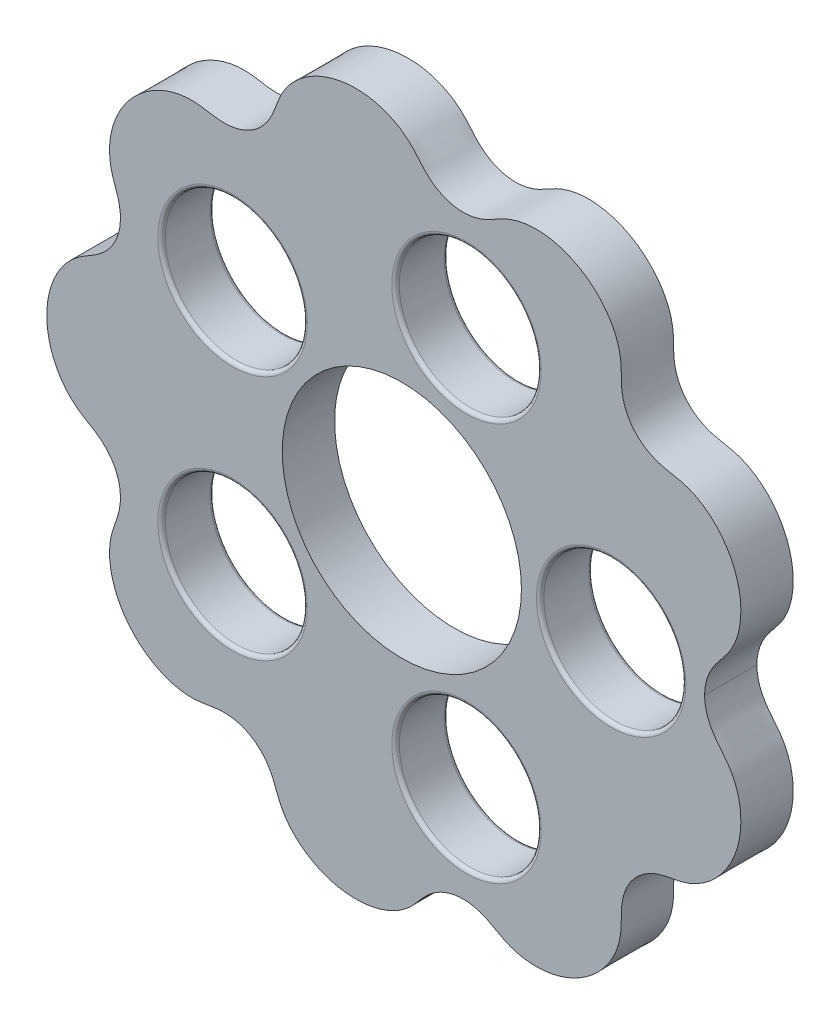
SolidWorks part; units mm, degrees
ref_plane "Front Plane" through (0, 0, 0) normal (0, 0, 1) x (1, 0, 0)
ref_plane "Top Plane" through (0, 0, 0) normal (0, 1, 0) x (1, 0, 0)
ref_plane "Right Plane" through (0, 0, 0) normal (1, 0, 0) x (0, 0, -1)
sketch "Sketch5" plane through (0, 0, 0) normal (0, 0, 1) x (1, 0, 0)
  line L0 (56.1295, 0) -> (-56.1295, 0) construction
  spline S0 degree 4 poles (43.9675, 24.717) (44.1687, 24.5903) (44.5645, 24.3264) (45.3286, 23.7583) (46.2192, 22.9456) (47.0351, 22.0389) (47.767, 21.0472) (48.3047, 20.1937) (48.7789, 19.3035) (49.1875, 18.3813) (49.5288, 17.4321) (49.8009, 16.4608) (50.0022, 15.4725) (50.1309, 14.4718) (50.1857, 13.465) (50.1646, 12.4557) (50.0754, 11.5375) (49.9355, 10.7086) (49.7662, 9.9782) (49.6126, 9.4514) (49.4889, 9.0812) (49.4028, 8.8445) (49.3404, 8.6786) (49.2593, 8.4723) (49.2112, 8.355) (49.1184, 8.1404) (49.0342, 7.9528) (48.9526, 7.7785) (48.8555, 7.5808) (48.7377, 7.3519) (48.5852, 7.0696) (48.3939, 6.7364) (48.159, 6.3539) (47.8783, 5.925) (47.5899, 5.501) (47.272, 5.0371) (46.9336, 4.5268) (46.4972, 3.8088) (46.0481, 2.9005) (45.6825, 1.8227) (45.4869, 0.6102) (45.484, -0.5297) (45.6482, -1.6249) (45.9563, -2.6553) (46.3957, -3.633) (46.9384, -4.5527) (47.5411, -5.4294) (48.1406, -6.3054) (48.6904, -7.2258) (49.1655, -8.1979) (49.6395, -9.4396) (50.0276, -10.9696) (50.2323, -12.8006) (50.1376, -14.9024) (49.7158, -16.999) (48.9654, -19.0387) (47.6825, -21.3439) (46.1225, -23.1584) (44.4622, -24.4809) (42.8636, -25.3575) (41.8693, -25.7911) (40.8609, -26.1347) (39.8537, -26.4142) (38.8354, -26.6988) (37.8273, -27.0594) (36.854, -27.5373) (35.9432, -28.1497) (34.939, -29.061) (34.1314, -30.1487) (33.5539, -31.3627) (33.1995, -32.6385) (33.0289, -33.6766) (32.9288, -34.7173) (32.8268, -35.7531) (32.6605, -36.8007) (32.4035, -37.8498) (31.9667, -39.1228) (31.2657, -40.5767) (30.227, -42.1296) (28.7855, -43.6836) (27.1062, -45.0123) (25.2246, -46.0808) (22.759, -47.0129) (20.3921, -47.3918) (18.2669, -47.3281) (16.4777, -46.9628) (15.4371, -46.6501) (14.4437, -46.2601) (13.4918, -45.8241) (12.526, -45.3893) (11.5179, -45.0232) (10.4613, -44.7719) (9.3672, -44.6655) (8.0168, -44.7313) (6.7093, -45.0558) (5.5003, -45.619) (4.4257, -46.3648) (3.6406, -47.0418) (2.7268, -47.9414) (1.7917, -48.8513) (0.7375, -49.6733) (-0.6219, -50.4978) (-2.0723, -51.1567) (-3.833, -51.6803) (-5.8932, -51.9573) (-7.9905, -51.9206) (-10.0775, -51.5666) (-12.088, -50.903) (-13.9742, -49.9397) (-15.4824, -48.8394) (-16.6398, -47.7163) (-17.4875, -46.6721) (-18.0894, -45.7762) (-18.6055, -44.8504) (-19.0563, -43.9131) (-19.505, -42.9697) (-20.0175, -42.052) (-20.7823, -40.9724) (-21.7356, -40.0254) (-22.8628, -39.2744) (-24.1159, -38.7557) (-25.181, -38.4871) (-26.2594, -38.3667) (-27.331, -38.3696) (-28.3861, -38.4493) (-29.4288, -38.5322) (-30.4948, -38.5564) (-31.5784, -38.4915) (-33.3824, -38.2183) (-35.3977, -37.547) (-37.488, -36.3782) (-39.4819, -34.6563) (-40.8817, -33.0063) (-42.0024, -31.1805) (-42.8224, -29.2237) (-43.2634, -27.4068) (-43.4214, -25.7988) (-43.3867, -24.1917) (-43.2006, -22.8598) (-42.8734, -21.5791) (-42.5465, -20.3141) (-42.3555, -19.2784) (-42.2772, -18.2222) (-42.3378, -17.1586) (-42.5473, -16.1081) (-42.909, -15.0934) (-43.4171, -14.138) (-44.0594, -13.2614) (-44.8022, -12.4895) (-45.614, -11.8151) (-46.4585, -11.2086) (-47.2938, -10.6137) (-48.1184, -9.9558) (-48.9082, -9.2134) (-49.6274, -8.4019) (-50.27, -7.5287) (-50.8209, -6.6283) (-51.2848, -5.7121) (-51.6811, -4.7493) (-52.0054, -3.745) (-52.2537, -2.7045) (-52.4219, -1.6338) (-52.5132, -0.4683) (-52.5053, 0.6082) (-52.4229, 1.588) (-52.2881, 2.4676) (-52.1443, 3.1648) (-51.9645, 3.8537) (-51.7758, 4.4473) (-51.5919, 4.9485) (-51.4091, 5.3965) (-51.2326, 5.7933) (-51.0254, 6.2185) (-50.7825, 6.6702) (-50.5225, 7.111) (-50.2433, 7.5422) (-49.9859, 7.9069) (-49.7512, 8.2152) (-49.5733, 8.4365) (-49.4505, 8.5837) (-49.3167, 8.7389) (-49.1732, 8.9007) (-49.0859, 8.996) (-48.9341, 9.1566) (-48.7865, 9.3083) (-48.6467, 9.4473) (-48.4833, 9.6035) (-48.2876, 9.7838) (-48.0399, 10.0026) (-47.7361, 10.2569) (-47.3725, 10.5432) (-46.9482, 10.8582) (-46.5187, 11.1664) (-46.0586, 11.4965) (-45.5745, 11.8581) (-44.9448, 12.3709) (-44.2444, 13.0481) (-43.5571, 13.907) (-42.9254, 15.0287) (-42.4873, 16.2586) (-42.2842, 17.5197) (-42.2956, 18.7647) (-42.4587, 19.9025) (-42.6702, 20.801) (-42.8707, 21.5656) (-42.9963, 22.0776) (-43.0549, 22.3346) (-43.083, 22.4633) knots 0 0 0 0 0 0.004209 0.008419 0.016838 0.021298 0.025758 0.030218 0.034678 0.039138 0.043598 0.048058 0.052519 0.056979 0.061439 0.065899 0.070359 0.073315 0.076272 0.079229 0.079968 0.080337 0.080707 0.082185 0.08332 0.083887 0.084454 0.085589 0.086723 0.087857 0.088992 0.091261 0.09353 0.095799 0.098067 0.100336 0.103486 0.106636 0.112936 0.118237 0.123537 0.128285 0.133033 0.137774 0.142514 0.147212 0.151909 0.156607 0.161304 0.166171 0.171038 0.180103 0.189168 0.198651 0.208135 0.217812 0.227489 0.245161 0.250125 0.255089 0.259714 0.26434 0.268966 0.273592 0.278429 0.283265 0.28811 0.292954 0.30235 0.307042 0.311735 0.31634 0.320946 0.325551 0.330156 0.335099 0.340042 0.349343 0.358644 0.368028 0.377413 0.387105 0.396798 0.414499 0.419471 0.424443 0.429077 0.433711 0.438344 0.442978 0.447822 0.452667 0.457519 0.462371 0.47167 0.476315 0.480961 0.485476 0.489992 0.499022 0.504042 0.509062 0.518101 0.527139 0.536428 0.545716 0.555093 0.56447 0.573764 0.583058 0.587998 0.592937 0.597539 0.602141 0.606743 0.611345 0.616033 0.620722 0.63011 0.634958 0.639806 0.644647 0.649487 0.654116 0.658746 0.663375 0.668005 0.672972 0.67794 0.695625 0.70531 0.714994 0.724386 0.733779 0.743088 0.752398 0.757345 0.762292 0.771511 0.77612 0.78073 0.785426 0.790123 0.794825 0.799527 0.804326 0.809124 0.813913 0.818702 0.82324 0.827778 0.832317 0.836855 0.841899 0.846943 0.851483 0.856023 0.860563 0.865103 0.869895 0.874687 0.879479 0.884271 0.89057 0.893719 0.896868 0.900017 0.903166 0.906315 0.90789 0.909465 0.911732 0.913999 0.916266 0.918534 0.920801 0.923068 0.924202 0.925335 0.925902 0.926469 0.927603 0.928772 0.929357 0.929942 0.931111 0.932281 0.933451 0.93462 0.936959 0.939299 0.941638 0.943977 0.946316 0.949324 0.952331 0.958347 0.96353 0.968712 0.975025 0.981338 0.986003 0.990669 0.995334 0.997667 1 1 1 1 1 construction
  spline S1 degree 4 poles (45.5, 0) (45.5, -0.2738) (45.5269, -0.8158) (45.6466, -1.6196) (45.9563, -2.6553) (46.3957, -3.633) (46.9384, -4.5527) (47.5411, -5.4294) (48.1406, -6.3054) (48.6904, -7.2258) (49.1655, -8.1979) (49.6395, -9.4396) (50.0276, -10.9696) (50.2323, -12.8006) (50.1376, -14.9024) (49.7158, -16.999) (48.9654, -19.0387) (47.6825, -21.3439) (46.1225, -23.1584) (44.4622, -24.4809) (42.8636, -25.3575) (41.8693, -25.7911) (40.8609, -26.1347) (39.8537, -26.4142) (38.8354, -26.6988) (37.8273, -27.0594) (36.854, -27.5373) (35.9432, -28.1497) (34.939, -29.061) (34.1314, -30.1487) (33.5539, -31.3627) (33.1995, -32.6385) (33.0289, -33.6766) (32.9288, -34.7173) (32.8268, -35.7531) (32.6605, -36.8007) (32.4035, -37.8498) (31.9667, -39.1228) (31.2657, -40.5767) (30.227, -42.1296) (28.7855, -43.6836) (27.1062, -45.0123) (25.2246, -46.0808) (22.759, -47.0129) (20.3921, -47.3918) (18.2669, -47.3281) (16.4777, -46.9628) (15.4371, -46.6501) (14.4437, -46.2601) (13.4918, -45.8241) (12.526, -45.3893) (11.5179, -45.0232) (10.4613, -44.7719) (9.3672, -44.6655) (8.0168, -44.7313) (6.7093, -45.0558) (5.5003, -45.619) (4.4257, -46.3648) (3.6406, -47.0418) (2.7268, -47.9414) (1.7917, -48.8513) (0.7375, -49.6733) (-0.6219, -50.4978) (-2.0723, -51.1567) (-3.833, -51.6803) (-5.8932, -51.9573) (-7.9905, -51.9206) (-10.0775, -51.5666) (-12.088, -50.903) (-13.9742, -49.9397) (-15.4824, -48.8394) (-16.6398, -47.7163) (-17.4875, -46.6721) (-18.0894, -45.7762) (-18.6055, -44.8504) (-19.0563, -43.9131) (-19.505, -42.9697) (-20.0175, -42.052) (-20.7823, -40.9724) (-21.7356, -40.0254) (-22.8628, -39.2744) (-24.1159, -38.7557) (-25.181, -38.4871) (-26.2594, -38.3667) (-27.331, -38.3696) (-28.3861, -38.4493) (-29.4288, -38.5322) (-30.4948, -38.5564) (-31.5784, -38.4915) (-33.3824, -38.2183) (-35.3977, -37.547) (-37.488, -36.3782) (-39.4819, -34.6563) (-40.8817, -33.0063) (-42.0024, -31.1805) (-42.8224, -29.2237) (-43.2634, -27.4068) (-43.4214, -25.7988) (-43.3867, -24.1917) (-43.2006, -22.8598) (-42.8734, -21.5791) (-42.5465, -20.3141) (-42.3555, -19.2784) (-42.2772, -18.2222) (-42.3378, -17.1586) (-42.5473, -16.1081) (-42.909, -15.0934) (-43.4171, -14.138) (-44.0594, -13.2614) (-44.8022, -12.4895) (-45.614, -11.8151) (-46.4585, -11.2086) (-47.2938, -10.6137) (-48.1184, -9.9558) (-48.9082, -9.2134) (-49.6274, -8.4019) (-50.27, -7.5287) (-50.8209, -6.6283) (-51.2848, -5.7121) (-51.6811, -4.7493) (-52.0054, -3.745) (-52.3172, -2.4382) (-52.4578, -1.3591) (-52.5, -0.5442) (-52.5, 0) knots 0.123439 0.123439 0.123439 0.123439 0.123439 0.128285 0.133033 0.137774 0.142514 0.147212 0.151909 0.156607 0.161304 0.166171 0.171038 0.180103 0.189168 0.198651 0.208135 0.217812 0.227489 0.245161 0.250125 0.255089 0.259714 0.26434 0.268966 0.273592 0.278429 0.283265 0.28811 0.292954 0.30235 0.307042 0.311735 0.31634 0.320946 0.325551 0.330156 0.335099 0.340042 0.349343 0.358644 0.368028 0.377413 0.387105 0.396798 0.414499 0.419471 0.424443 0.429077 0.433711 0.438344 0.442978 0.447822 0.452667 0.457519 0.462371 0.47167 0.476315 0.480961 0.485476 0.489992 0.499022 0.504042 0.509062 0.518101 0.527139 0.536428 0.545716 0.555093 0.56447 0.573764 0.583058 0.587998 0.592937 0.597539 0.602141 0.606743 0.611345 0.616033 0.620722 0.63011 0.634958 0.639806 0.644647 0.649487 0.654116 0.658746 0.663375 0.668005 0.672972 0.67794 0.695625 0.70531 0.714994 0.724386 0.733779 0.743088 0.752398 0.757345 0.762292 0.771511 0.77612 0.78073 0.785426 0.790123 0.794825 0.799527 0.804326 0.809124 0.813913 0.818702 0.82324 0.827778 0.832317 0.836855 0.841899 0.846943 0.851483 0.856023 0.860563 0.865103 0.869895 0.874687 0.884321 0.884321 0.884321 0.884321 0.884321 construction
  spline S2 degree 4 poles (45.5, 0) (45.5, 0.2738) (45.5269, 0.8158) (45.6466, 1.6196) (45.9563, 2.6553) (46.3957, 3.633) (46.9384, 4.5527) (47.5411, 5.4294) (48.1406, 6.3054) (48.6904, 7.2258) (49.1655, 8.1979) (49.6395, 9.4396) (50.0276, 10.9696) (50.2323, 12.8006) (50.1376, 14.9024) (49.7158, 16.999) (48.9654, 19.0387) (47.6825, 21.3439) (46.1225, 23.1584) (44.4622, 24.4809) (42.8636, 25.3575) (41.8693, 25.7911) (40.8609, 26.1347) (39.8537, 26.4142) (38.8354, 26.6988) (37.8273, 27.0594) (36.854, 27.5373) (35.9432, 28.1497) (34.939, 29.061) (34.1314, 30.1487) (33.5539, 31.3627) (33.1995, 32.6385) (33.0289, 33.6766) (32.9288, 34.7173) (32.8268, 35.7531) (32.6605, 36.8007) (32.4035, 37.8498) (31.9667, 39.1228) (31.2657, 40.5767) (30.227, 42.1296) (28.7855, 43.6836) (27.1062, 45.0123) (25.2246, 46.0808) (22.759, 47.0129) (20.3921, 47.3918) (18.2669, 47.3281) (16.4777, 46.9628) (15.4371, 46.6501) (14.4437, 46.2601) (13.4918, 45.8241) (12.526, 45.3893) (11.5179, 45.0232) (10.4613, 44.7719) (9.3672, 44.6655) (8.0168, 44.7313) (6.7093, 45.0558) (5.5003, 45.619) (4.4257, 46.3648) (3.6406, 47.0418) (2.7268, 47.9414) (1.7917, 48.8513) (0.7375, 49.6733) (-0.6219, 50.4978) (-2.0723, 51.1567) (-3.833, 51.6803) (-5.8932, 51.9573) (-7.9905, 51.9206) (-10.0775, 51.5666) (-12.088, 50.903) (-13.9742, 49.9397) (-15.4824, 48.8394) (-16.6398, 47.7163) (-17.4875, 46.6721) (-18.0894, 45.7762) (-18.6055, 44.8504) (-19.0563, 43.9131) (-19.505, 42.9697) (-20.0175, 42.052) (-20.7823, 40.9724) (-21.7356, 40.0254) (-22.8628, 39.2744) (-24.1159, 38.7557) (-25.181, 38.4871) (-26.2594, 38.3667) (-27.331, 38.3696) (-28.3861, 38.4493) (-29.4288, 38.5322) (-30.4948, 38.5564) (-31.5784, 38.4915) (-33.3824, 38.2183) (-35.3977, 37.547) (-37.488, 36.3782) (-39.4819, 34.6563) (-40.8817, 33.0063) (-42.0024, 31.1805) (-42.8224, 29.2237) (-43.2634, 27.4068) (-43.4214, 25.7988) (-43.3867, 24.1917) (-43.2006, 22.8598) (-42.8734, 21.5791) (-42.5465, 20.3141) (-42.3555, 19.2784) (-42.2772, 18.2222) (-42.3378, 17.1586) (-42.5473, 16.1081) (-42.909, 15.0934) (-43.4171, 14.138) (-44.0594, 13.2614) (-44.8022, 12.4895) (-45.614, 11.8151) (-46.4585, 11.2086) (-47.2938, 10.6137) (-48.1184, 9.9558) (-48.9082, 9.2134) (-49.6274, 8.4019) (-50.27, 7.5287) (-50.8209, 6.6283) (-51.2848, 5.7121) (-51.6811, 4.7493) (-52.0054, 3.745) (-52.3172, 2.4382) (-52.4578, 1.3591) (-52.5, 0.5442) (-52.5, 0) knots 0.123439 0.123439 0.123439 0.123439 0.123439 0.128285 0.133033 0.137774 0.142514 0.147212 0.151909 0.156607 0.161304 0.166171 0.171038 0.180103 0.189168 0.198651 0.208135 0.217812 0.227489 0.245161 0.250125 0.255089 0.259714 0.26434 0.268966 0.273592 0.278429 0.283265 0.28811 0.292954 0.30235 0.307042 0.311735 0.31634 0.320946 0.325551 0.330156 0.335099 0.340042 0.349343 0.358644 0.368028 0.377413 0.387105 0.396798 0.414499 0.419471 0.424443 0.429077 0.433711 0.438344 0.442978 0.447822 0.452667 0.457519 0.462371 0.47167 0.476315 0.480961 0.485476 0.489992 0.499022 0.504042 0.509062 0.518101 0.527139 0.536428 0.545716 0.555093 0.56447 0.573764 0.583058 0.587998 0.592937 0.597539 0.602141 0.606743 0.611345 0.616033 0.620722 0.63011 0.634958 0.639806 0.644647 0.649487 0.654116 0.658746 0.663375 0.668005 0.672972 0.67794 0.695625 0.70531 0.714994 0.724386 0.733779 0.743088 0.752398 0.757345 0.762292 0.771511 0.77612 0.78073 0.785426 0.790123 0.794825 0.799527 0.804326 0.809124 0.813913 0.818702 0.82324 0.827778 0.832317 0.836855 0.841899 0.846943 0.851483 0.856023 0.860563 0.865103 0.869895 0.874687 0.884321 0.884321 0.884321 0.884321 0.884321
  spline S3 degree 4 poles (39.5766, 22.3085) (39.8004, 22.1855) (40.2393, 21.9239) (40.8701, 21.4868) (41.6504, 20.8253) (42.3931, 20.0658) (43.0854, 19.2087) (43.7136, 18.2559) (44.194, 17.3414) (44.5404, 16.5271) (44.8328, 15.6925) (45.0308, 14.9822) (45.1819, 14.2605) (45.3056, 13.3848) (45.3599, 12.6494) (45.3641, 11.912) (45.3135, 11.1209) (45.2271, 10.4253) (45.1019, 9.7816) (44.9473, 9.1927) (44.8074, 8.7572) (44.7044, 8.4704) (44.6232, 8.2616) (44.5625, 8.1149) (44.4976, 7.9642) (44.4318, 7.8165) (44.3851, 7.7164) (44.3122, 7.5671) (44.235, 7.4141) (44.1585, 7.2686) (44.0705, 7.1098) (43.9641, 6.9272) (43.8252, 6.7007) (43.651, 6.435) (43.4364, 6.1323) (43.1781, 5.7961) (42.9105, 5.4674) (42.5879, 5.0811) (42.2182, 4.6306) (41.7093, 3.9521) (41.166, 3.0382) (40.722, 1.923) (40.4882, 0.6701) (40.4796, -0.4914) (40.653, -1.5793) (40.9703, -2.5716) (41.5084, -3.6724) (42.3244, -4.8199) (43.4581, -6.04) (44.4394, -7.6395) (45.0781, -9.416) (45.3935, -11.3531) (45.3733, -13.3153) (45.0109, -15.3119) (44.2879, -17.2786) (43.2692, -19.036) (42.0084, -20.545) (40.7094, -21.6461) (39.4845, -22.3999) (38.3839, -22.8844) (37.4599, -23.1769) (36.3352, -23.4155) (35.1998, -23.589) (34.0478, -23.9056) (32.6897, -24.5345) (31.4105, -25.469) (30.4061, -26.7091) (29.759, -28.1519) (29.4231, -29.5922) (29.3287, -30.9744) (29.4038, -32.6176) (29.1221, -34.4497) (28.4703, -36.2081) (27.4614, -37.895) (26.1801, -39.3847) (24.608, -40.684) (22.771, -41.7281) (20.842, -42.4149) (18.8892, -42.7494) (17.1745, -42.7433) (15.7452, -42.5178) (14.5921, -42.1671) (13.7044, -41.7878) (12.7082, -41.2467) (11.5114, -40.5262) (9.9117, -39.8725) (7.8846, -39.6519) (6.0646, -40.0262) (4.6603, -40.7212) (3.5017, -41.5984) (2.5562, -42.5823) (1.5724, -43.868) (0.2013, -45.0812) (-1.4073, -46.0098) (-3.2386, -46.6589) (-5.1527, -46.988) (-7.1616, -46.9931) (-9.2067, -46.6457) (-11.1104, -45.9727) (-12.8232, -45.0159) (-14.3493, -43.7814) (-15.5652, -42.3575) (-16.462, -40.738) (-16.9556, -39.1709) (-17.5096, -37.9041) (-18.1696, -36.8831) (-18.8559, -36.0951) (-19.8582, -35.2473) (-21.2523, -34.4926) (-22.7663, -34.1275) (-24.2685, -34.1297) (-25.4483, -34.294) (-26.3216, -34.4559) (-27.2413, -34.588) (-28.2108, -34.6329) (-29.4128, -34.5578) (-30.8244, -34.272) (-32.4254, -33.6847) (-34.1307, -32.7001) (-35.6958, -31.3961) (-37.0554, -29.7901) (-38.0832, -28.0317) (-38.7746, -26.1887) (-39.1404, -24.2544) (-39.1456, -22.3756) (-38.7743, -20.5568) (-38.1381, -19.037) (-37.7608, -17.7012) (-37.592, -16.2294) (-37.7184, -14.6458) (-38.2538, -13.1318) (-39.1565, -11.8152) (-40.2312, -10.7698) (-41.3844, -9.9676) (-42.6302, -9.3285) (-43.7677, -8.5031) (-44.6232, -7.6775) (-45.2512, -6.9289) (-45.782, -6.1595) (-46.2253, -5.3838) (-46.6211, -4.5372) (-46.9589, -3.6209) (-47.227, -2.6387) (-47.4135, -1.5955) (-47.5127, -0.4796) (-47.5058, 0.7018) (-47.3905, 1.7752) (-47.1986, 2.7327) (-46.9805, 3.5162) (-46.7711, 4.1323) (-46.547, 4.6862) (-46.3169, 5.1795) (-46.089, 5.6145) (-45.87, 5.994) (-45.6357, 6.364) (-45.3857, 6.7241) (-45.1543, 7.0288) (-44.9446, 7.2843) (-44.7866, 7.4663) (-44.6733, 7.5912) (-44.5523, 7.7203) (-44.4331, 7.844) (-44.354, 7.9233) (-44.2358, 8.0374) (-44.1157, 8.1505) (-43.998, 8.258) (-43.8285, 8.4062) (-43.5924, 8.6013) (-43.3085, 8.819) (-42.9747, 9.053) (-42.6316, 9.2747) (-42.2825, 9.4857) (-41.8549, 9.7349) (-41.3528, 10.0287) (-40.6295, 10.4901) (-39.795, 11.1552) (-38.9909, 12.0337) (-38.2898, 13.177) (-37.829, 14.3966) (-37.6286, 15.5914) (-37.6363, 16.7071) (-37.781, 17.6865) (-37.97, 18.4203) (-38.1733, 19.0363) (-38.3193, 19.4432) (-38.392, 19.6467) (-38.4284, 19.7485) knots 0 0 0 0 0 0.004925 0.00985 0.014774 0.019699 0.025382 0.031065 0.036747 0.039589 0.04243 0.048113 0.050954 0.053796 0.059478 0.06232 0.065161 0.069076 0.07299 0.074947 0.076905 0.077883 0.078862 0.079351 0.079841 0.080819 0.081841 0.082352 0.082863 0.083884 0.084906 0.085928 0.08695 0.088993 0.091037 0.09308 0.095124 0.097167 0.100743 0.104319 0.11147 0.117607 0.123744 0.128753 0.133762 0.138765 0.143768 0.152292 0.160815 0.170819 0.179647 0.188474 0.198478 0.208482 0.218584 0.228686 0.237453 0.246219 0.25127 0.25632 0.260596 0.264872 0.273424 0.278472 0.283519 0.293637 0.303708 0.308735 0.313762 0.322052 0.330342 0.340399 0.3492 0.358001 0.368058 0.378115 0.388332 0.398548 0.407341 0.416134 0.421242 0.426349 0.430533 0.434718 0.443086 0.453298 0.46353 0.473409 0.47834 0.48327 0.491457 0.499644 0.509508 0.518286 0.527063 0.536928 0.546792 0.556835 0.566878 0.575666 0.584455 0.594499 0.602778 0.611057 0.616076 0.621094 0.626123 0.631151 0.641282 0.65139 0.655673 0.659955 0.664238 0.66852 0.673578 0.678635 0.687414 0.696193 0.706309 0.716425 0.726499 0.736573 0.745388 0.754204 0.764278 0.772581 0.780884 0.78592 0.790956 0.801044 0.811264 0.816368 0.821471 0.829854 0.838237 0.843339 0.848442 0.852744 0.857045 0.861347 0.865648 0.870751 0.875853 0.880956 0.886058 0.892329 0.898599 0.901735 0.90487 0.908005 0.911141 0.913252 0.915363 0.917475 0.919586 0.921698 0.923809 0.924865 0.92592 0.926448 0.926976 0.928032 0.929015 0.929507 0.929999 0.930983 0.931966 0.933934 0.935901 0.937868 0.939836 0.941803 0.94377 0.947412 0.951054 0.958338 0.964286 0.970233 0.976779 0.983325 0.987494 0.991663 0.995831 0.997916 1 1 1 1 1 construction
  spline S4 degree 4 poles (40.5, 0) (40.5, -0.2667) (40.5277, -0.7931) (40.6509, -1.5727) (40.9703, -2.5716) (41.5084, -3.6724) (42.3244, -4.8199) (43.4581, -6.04) (44.4394, -7.6395) (45.0781, -9.416) (45.3935, -11.3531) (45.3733, -13.3153) (45.0109, -15.3119) (44.2879, -17.2786) (43.2692, -19.036) (42.0084, -20.545) (40.7094, -21.6461) (39.4845, -22.3999) (38.3839, -22.8844) (37.4599, -23.1769) (36.3352, -23.4155) (35.1998, -23.589) (34.0478, -23.9056) (32.6897, -24.5345) (31.4105, -25.469) (30.4061, -26.7091) (29.759, -28.1519) (29.4231, -29.5922) (29.3287, -30.9744) (29.4038, -32.6176) (29.1221, -34.4497) (28.4703, -36.2081) (27.4614, -37.895) (26.1801, -39.3847) (24.608, -40.684) (22.771, -41.7281) (20.842, -42.4149) (18.8892, -42.7494) (17.1745, -42.7433) (15.7452, -42.5178) (14.5921, -42.1671) (13.7044, -41.7878) (12.7082, -41.2467) (11.5114, -40.5262) (9.9117, -39.8725) (7.8846, -39.6519) (6.0646, -40.0262) (4.6603, -40.7212) (3.5017, -41.5984) (2.5562, -42.5823) (1.5724, -43.868) (0.2013, -45.0812) (-1.4073, -46.0098) (-3.2386, -46.6589) (-5.1527, -46.988) (-7.1616, -46.9931) (-9.2067, -46.6457) (-11.1104, -45.9727) (-12.8232, -45.0159) (-14.3493, -43.7814) (-15.5652, -42.3575) (-16.462, -40.738) (-16.9556, -39.1709) (-17.5096, -37.9041) (-18.1696, -36.8831) (-18.8559, -36.0951) (-19.8582, -35.2473) (-21.2523, -34.4926) (-22.7663, -34.1275) (-24.2685, -34.1297) (-25.4483, -34.294) (-26.3216, -34.4559) (-27.2413, -34.588) (-28.2108, -34.6329) (-29.4128, -34.5578) (-30.8244, -34.272) (-32.4254, -33.6847) (-34.1307, -32.7001) (-35.6958, -31.3961) (-37.0554, -29.7901) (-38.0832, -28.0317) (-38.7746, -26.1887) (-39.1404, -24.2544) (-39.1456, -22.3756) (-38.7743, -20.5568) (-38.1381, -19.037) (-37.7608, -17.7012) (-37.592, -16.2294) (-37.7184, -14.6458) (-38.2538, -13.1318) (-39.1565, -11.8152) (-40.2312, -10.7698) (-41.3844, -9.9676) (-42.6302, -9.3285) (-43.7677, -8.5031) (-44.6232, -7.6775) (-45.2512, -6.9289) (-45.782, -6.1595) (-46.2253, -5.3838) (-46.6211, -4.5372) (-46.9589, -3.6209) (-47.227, -2.6387) (-47.414, -1.593) (-47.4843, -0.7988) (-47.5, -0.2671) (-47.5, 0) knots 0.12361 0.12361 0.12361 0.12361 0.12361 0.128753 0.133762 0.138765 0.143768 0.152292 0.160815 0.170819 0.179647 0.188474 0.198478 0.208482 0.218584 0.228686 0.237453 0.246219 0.25127 0.25632 0.260596 0.264872 0.273424 0.278472 0.283519 0.293637 0.303708 0.308735 0.313762 0.322052 0.330342 0.340399 0.3492 0.358001 0.368058 0.378115 0.388332 0.398548 0.407341 0.416134 0.421242 0.426349 0.430533 0.434718 0.443086 0.453298 0.46353 0.473409 0.47834 0.48327 0.491457 0.499644 0.509508 0.518286 0.527063 0.536928 0.546792 0.556835 0.566878 0.575666 0.584455 0.594499 0.602778 0.611057 0.616076 0.621094 0.626123 0.631151 0.641282 0.65139 0.655673 0.659955 0.664238 0.66852 0.673578 0.678635 0.687414 0.696193 0.706309 0.716425 0.726499 0.736573 0.745388 0.754204 0.764278 0.772581 0.780884 0.78592 0.790956 0.801044 0.811264 0.816368 0.821471 0.829854 0.838237 0.843339 0.848442 0.852744 0.857045 0.861347 0.865648 0.870751 0.875853 0.880956 0.886107 0.886107 0.886107 0.886107 0.886107
  spline S5 degree 4 poles (40.5, 0) (40.5, 0.2667) (40.5277, 0.7931) (40.6509, 1.5727) (40.9703, 2.5716) (41.5084, 3.6724) (42.3244, 4.8199) (43.4581, 6.04) (44.4394, 7.6395) (45.0781, 9.416) (45.3935, 11.3531) (45.3733, 13.3153) (45.0109, 15.3119) (44.2879, 17.2786) (43.2692, 19.036) (42.0084, 20.545) (40.7094, 21.6461) (39.4845, 22.3999) (38.3839, 22.8844) (37.4599, 23.1769) (36.3352, 23.4155) (35.1998, 23.589) (34.0478, 23.9056) (32.6897, 24.5345) (31.4105, 25.469) (30.4061, 26.7091) (29.759, 28.1519) (29.4231, 29.5922) (29.3287, 30.9744) (29.4038, 32.6176) (29.1221, 34.4497) (28.4703, 36.2081) (27.4614, 37.895) (26.1801, 39.3847) (24.608, 40.684) (22.771, 41.7281) (20.842, 42.4149) (18.8892, 42.7494) (17.1745, 42.7433) (15.7452, 42.5178) (14.5921, 42.1671) (13.7044, 41.7878) (12.7082, 41.2467) (11.5114, 40.5262) (9.9117, 39.8725) (7.8846, 39.6519) (6.0646, 40.0262) (4.6603, 40.7212) (3.5017, 41.5984) (2.5562, 42.5823) (1.5724, 43.868) (0.2013, 45.0812) (-1.4073, 46.0098) (-3.2386, 46.6589) (-5.1527, 46.988) (-7.1617, 46.9931) (-9.2067, 46.6457) (-11.1104, 45.9727) (-12.8232, 45.0159) (-14.3493, 43.7814) (-15.5652, 42.3575) (-16.462, 40.738) (-16.9556, 39.1709) (-17.5096, 37.9041) (-18.1696, 36.8831) (-18.8559, 36.0951) (-19.8582, 35.2473) (-21.2523, 34.4926) (-22.7663, 34.1275) (-24.2685, 34.1297) (-25.4483, 34.294) (-26.3216, 34.4559) (-27.2413, 34.588) (-28.2108, 34.6329) (-29.4128, 34.5578) (-30.8244, 34.272) (-32.4254, 33.6847) (-34.1307, 32.7001) (-35.6958, 31.3961) (-37.0554, 29.7901) (-38.0832, 28.0317) (-38.7746, 26.1887) (-39.1404, 24.2544) (-39.1456, 22.3756) (-38.7743, 20.5568) (-38.1381, 19.037) (-37.7608, 17.7012) (-37.592, 16.2294) (-37.7184, 14.6458) (-38.2538, 13.1318) (-39.1565, 11.8152) (-40.2312, 10.7698) (-41.3844, 9.9676) (-42.6302, 9.3285) (-43.7677, 8.5031) (-44.6232, 7.6775) (-45.2512, 6.9289) (-45.782, 6.1595) (-46.2253, 5.3838) (-46.6211, 4.5372) (-46.9589, 3.6209) (-47.227, 2.6387) (-47.414, 1.593) (-47.4843, 0.7988) (-47.5, 0.2671) (-47.5, 0) knots 0.12361 0.12361 0.12361 0.12361 0.12361 0.128753 0.133762 0.138765 0.143768 0.152292 0.160815 0.170819 0.179647 0.188474 0.198478 0.208482 0.218584 0.228686 0.237453 0.246219 0.25127 0.25632 0.260596 0.264872 0.273424 0.278472 0.283519 0.293637 0.303708 0.308735 0.313762 0.322052 0.330342 0.340399 0.3492 0.358001 0.368058 0.378115 0.388332 0.398548 0.407341 0.416134 0.421242 0.426349 0.430533 0.434718 0.443086 0.453298 0.46353 0.473409 0.47834 0.48327 0.491457 0.499644 0.509508 0.518286 0.527063 0.536928 0.546792 0.556835 0.566878 0.575666 0.584455 0.594499 0.602778 0.611057 0.616076 0.621094 0.626123 0.631151 0.641282 0.65139 0.655673 0.659955 0.664238 0.66852 0.673578 0.678635 0.687414 0.696193 0.706309 0.716425 0.726499 0.736573 0.745388 0.754204 0.764278 0.772581 0.780884 0.78592 0.790956 0.801044 0.811264 0.816368 0.821471 0.829854 0.838237 0.843339 0.848442 0.852744 0.857045 0.861347 0.865648 0.870751 0.875853 0.880956 0.886107 0.886107 0.886107 0.886107 0.886107
  point P8 (0, 0)
extrude "Boss-Extrude1" add sketch "Sketch5" along normal blind 7 contours S4 S5
sketch "Sketch6" plane through (0, 0, 7) normal (0, 0, 1) x (1, 0, 0)
  line L0 (0, 0) -> (-52.5, 0) construction
  line L1 (-16.25, 23.7805) -> (-16.25, -23.7805) construction
  line L2 (-18.75, 33.0294) -> (-18.75, -33.0294) construction
  line L3 (0, 0) -> (0, 62.3031) construction
  line L4 (0, 0) -> (-16.2234, 49.9305) construction
  line L5 (0, 0) -> (42.4734, 30.8587) construction
  line L6 (0, 0) -> (42.4734, -30.8587) construction
  line L7 (0, 0) -> (-16.2234, -49.9305) construction
  circle A0 centre (-28.25, 0) radius 9.5
  circle A2 centre (-8.7297, 26.8673) radius 9.5
  circle A3 centre (22.8547, 16.6049) radius 9.5
  circle A4 centre (22.8547, -16.6049) radius 9.5
  circle A5 centre (-8.7297, -26.8673) radius 9.5
  circle A6 centre (0, 0) radius 52.5 construction
  circle A7 centre (0, 0) radius 16.25 construction
  point P10 (-16.25, 0)
  point P12 (-18.75, 0)
  dimension "D1" = 19
  dimension "D2" = 32.5
  dimension "D5" = 105
  dimension "D3" = 2.5
  dimension "D4" = 5
extrude "Cut-Extrude1" [suppressed] cut sketch "Sketch6" against normal through all
sketch "Sketch8" plane through (0, 0, 7) normal (0, 0, 1) x (1, 0, 0)
  circle A0 centre (0, 0) radius 16
  dimension "D1" = 32
extrude "Cut-Extrude2" cut sketch "Sketch8" against normal blind 10
sketch "Sketch9" plane through (0, 0, 7) normal (0, 0, 1) x (1, 0, 0)
  line L0 (0, 0) -> (-42.4734, -30.8587) construction
  line L1 (2.3026, -34.6434) -> (-32.2362, 12.8953) construction
  line L2 (-24.6279, 6.6766) -> (-1.2607, -25.4857) construction
  line L3 (0, 0) -> (-42.4734, 30.8587) construction
  line L4 (0, 0) -> (16.2234, 49.9305) construction
  line L5 (0, 0) -> (52.5, 0) construction
  line L6 (0, 0) -> (16.2234, -49.9305) construction
  circle A0 centre (-22.6525, -16.458) radius 9.5
  circle A1 centre (0, 0) radius 16 construction
  circle A4 centre (0, 0) radius 52.5 construction
  circle A5 centre (-22.6525, 16.458) radius 9.5
  circle A6 centre (8.6525, 26.6296) radius 9.5
  circle A7 centre (28, 0) radius 9.5
  circle A8 centre (8.6525, -26.6296) radius 9.5
  point P9 (-14.9668, -10.874)
  point P10 (-12.9443, -9.4046)
  point P15 (-12.9443, -9.4046)
  dimension "D2" = 19
  dimension "D1" = 2.5
  dimension "D3" = 5
extrude "Cut-Extrude3" cut sketch "Sketch9" against normal through all
fillet "Fillet1" radius 0.5 10 edges at (18.1525, -26.6296, 0) (37.5, 0, 7) (37.5, 0, 0) (18.1525, 26.6296, 0) (18.1525, 26.6296, 7) (-13.1525, 16.458, 7) (-13.1525, 16.458, 0) (18.1525, -26.6296, 7) (-13.1525, -16.458, 7) (-13.1525, -16.458, 0)
